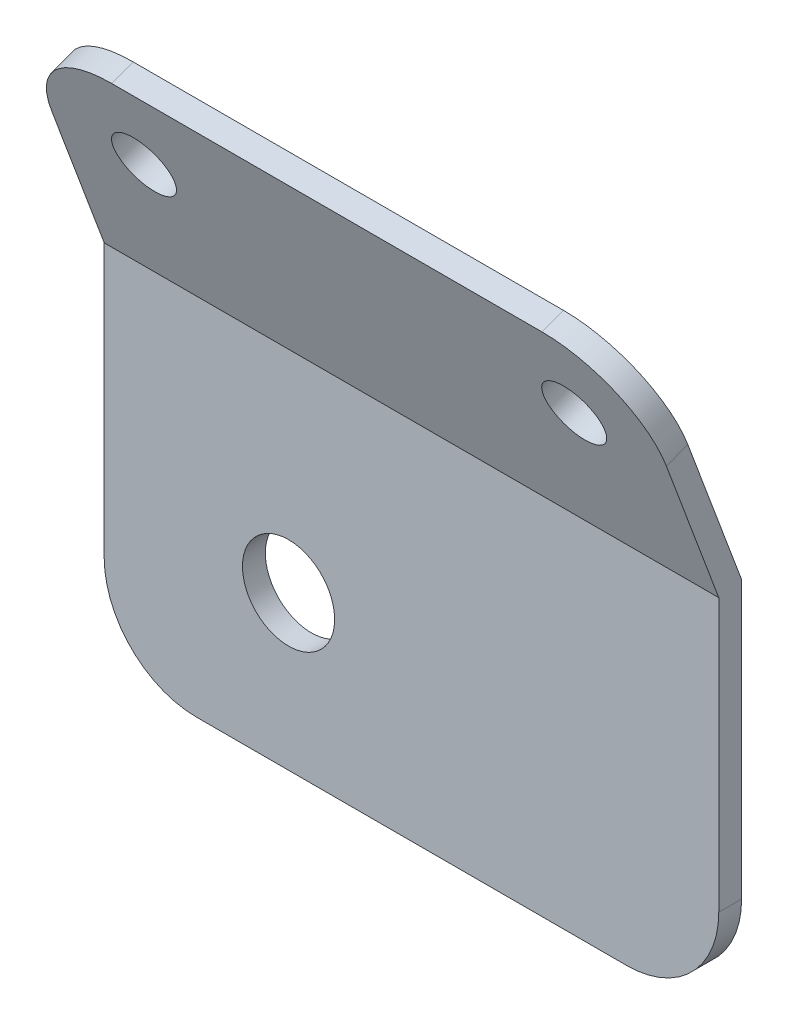
SolidWorks part; units mm, degrees
ref_plane "front" through (0, 0, 0) normal (0, 0, 1) x (1, 0, 0)
ref_plane "top" through (0, 0, 0) normal (0, 1, 0) x (1, 0, 0)
ref_plane "right" through (0, 0, 0) normal (1, 0, 0) x (0, 0, -1)
sketch "Sketch1" plane through (0, 0, 0) normal (1, 0, 0) x (0, 0, -1)
  line L0 (-8.8953, 23.7915) -> (0, 0)
  line L1 (0, 0) -> (0, -38.1)
  dimension "D1" = 25.4
  dimension "D2" = 38.1
  dimension "D3" = 20.5
extrude "Extrude-Thin1" add sketch "Sketch1" along normal mid plane 63.5 thin
sketch "Sketch2" plane through (0, 0, 0) normal (0, 0, -1) x (-1, 0, 0)
  line L0 (-31.75, -38.1) -> (31.75, -38.1) construction
  circle A0 centre (12.7, -22.225) radius 4.7625
  dimension "D2" = 9.525
  dimension "D1" = 15.875
  dimension "D3" = 12.7
extrude "Cut-Extrude1" cut sketch "Sketch2" against normal through all
sketch "Sketch3" plane through (0, 0, 0) normal (0, 0.3502, -0.9367) x (-1, 0, 0)
  line L0 (0, 0) -> (0, 17.78) construction
  line L1 (-31.75, 25.4) -> (31.75, 25.4) construction
  circle A0 centre (-22.225, 15.875) radius 3.175
  circle A1 centre (22.225, 15.875) radius 3.175
  dimension "D3" = 6.35
  dimension "D1" = 44.45
  dimension "D2" = 9.525
extrude "Cut-Extrude2" cut sketch "Sketch3" against normal through all
sketch "Sketch4" [suppressed] plane through (0, 0, 0) normal (0, -0.0785, 0.9969) x (1, 0, 0)
  circle A0 centre (-22.225, 15.875) radius 3.175 construction
  circle A1 centre (22.225, 15.875) radius 3.175 construction
  point P0 (22.225, 15.875)
  point P1 (-22.225, 15.875)
fillet "Fillet1" radius 9.525 4 edges at (-31.75, -38.1, 1.1811) (31.75, -38.1, 1.1811) (31.75, 23.3778, 10.0016) (-31.75, 23.3778, 10.0016)
